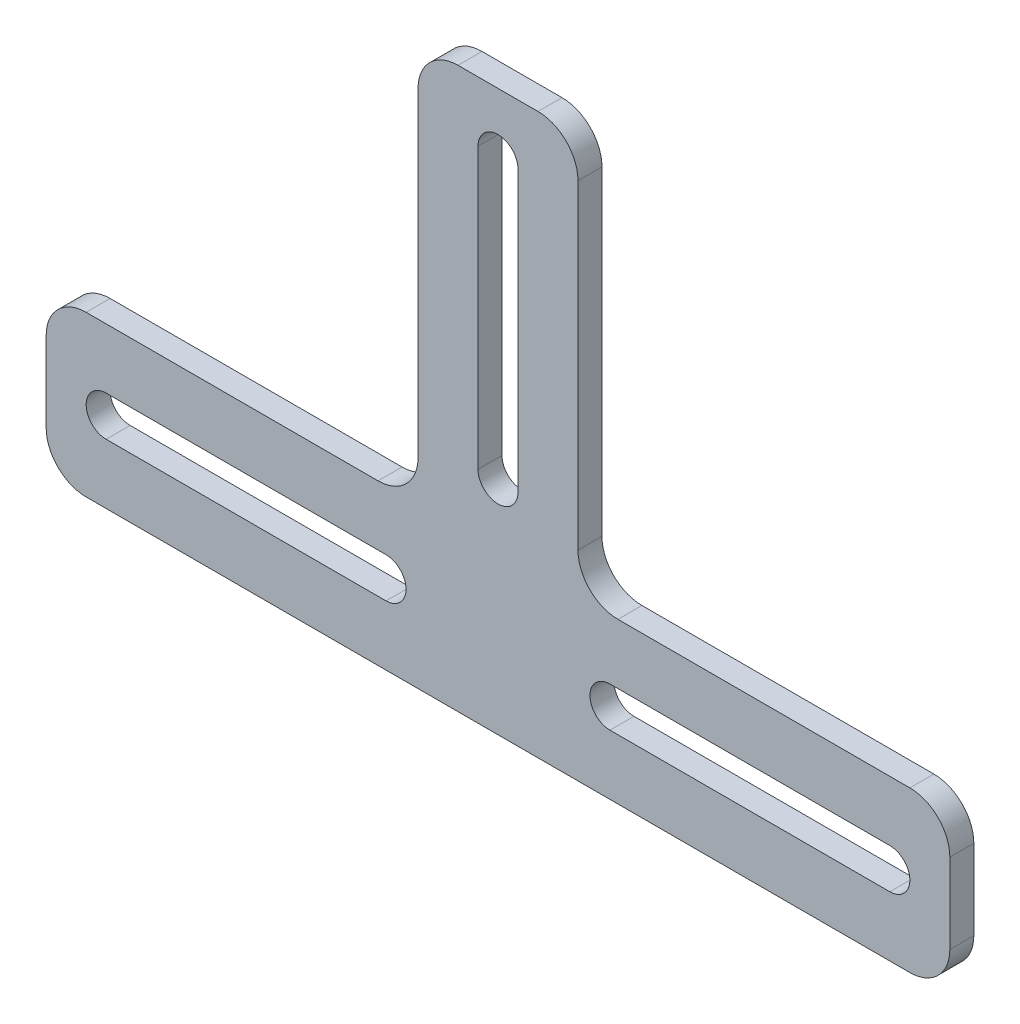
SolidWorks part; units mm, degrees
ref_plane "Front Plane" through (0, 0, 0) normal (0, 0, 1) x (1, 0, 0)
ref_plane "Top Plane" through (0, 0, 0) normal (0, 1, 0) x (1, 0, 0)
ref_plane "Right Plane" through (0, 0, 0) normal (1, 0, 0) x (0, 0, -1)
sketch "Sketch1" plane through (0, 0, 0) normal (0, 0, 1) x (1, 0, 0)
  line L0 (0, -396.3534) -> (0, 19421.3165) construction
  line L1 (-396.3534, 0) -> (19421.3165, 0) construction
  line L3 (0, 0) -> (56.5, 0)
  line L4 (56.5, 0) -> (56.5, 20)
  line L5 (56.5, 20) -> (10, 20)
  line L8 (0, 62.5) -> (0, 27.5) construction
  line L9 (2.5, 62.5) -> (2.5, 27.5)
  line L10 (-2.5, 62.5) -> (-2.5, 27.5)
  line L11 (49, 10) -> (14, 10) construction
  line L12 (49, 7.5) -> (14, 7.5)
  line L13 (49, 12.5) -> (14, 12.5)
  line L14 (-49, 10) -> (-14, 10) construction
  line L15 (-49, 7.5) -> (-14, 7.5)
  line L16 (-49, 12.5) -> (-14, 12.5)
  line L17 (-56.5, 20) -> (-10, 20)
  line L18 (-56.5, 0) -> (-56.5, 20)
  line L19 (0, 0) -> (-56.5, 0)
  line L22 (-10, 20) -> (-10, 70)
  line L23 (-10, 70) -> (10, 70)
  line L24 (10, 20) -> (10, 70)
  arc A0 (2.5, 62.5) -> (-2.5, 62.5) centre (0, 62.5) ccw
  arc A1 (-2.5, 27.5) -> (2.5, 27.5) centre (0, 27.5) ccw
  arc A2 (49, 7.5) -> (49, 12.5) centre (49, 10) ccw
  arc A3 (14, 12.5) -> (14, 7.5) centre (14, 10) ccw
  arc A4 (-49, 7.5) -> (-49, 12.5) centre (-49, 10) cw
  arc A5 (-14, 12.5) -> (-14, 7.5) centre (-14, 10) cw
  point P11 (28.25, 0)
  point P14 (0, 45)
  point P19 (31.5, 10)
  point P28 (56.5, 10)
  point P30 (-31.5, 10)
  point P36 (0, 70)
  point P39 (0, 0)
  point P40 (0, 0)
  dimension "D3" = 2.5
  dimension "D8" = 7.5
  dimension "D1" = 20
  dimension "D2" = 20
  dimension "D4" = 35
  dimension "D5" = 70
  dimension "D6" = 7.5
  dimension "D7" = 14
extrude "Boss-Extrude1" add sketch "Sketch1" along normal blind 3
fillet "Fillet1" radius 5 8 edges at (10, 20, 1.5) (56.5, 0, 1.5) (56.5, 20, 1.5) (-10, 20, 1.5) (-56.5, 0, 1.5) (-10, 70, 1.5) (10, 70, 1.5) (-56.5, 20, 1.5)
